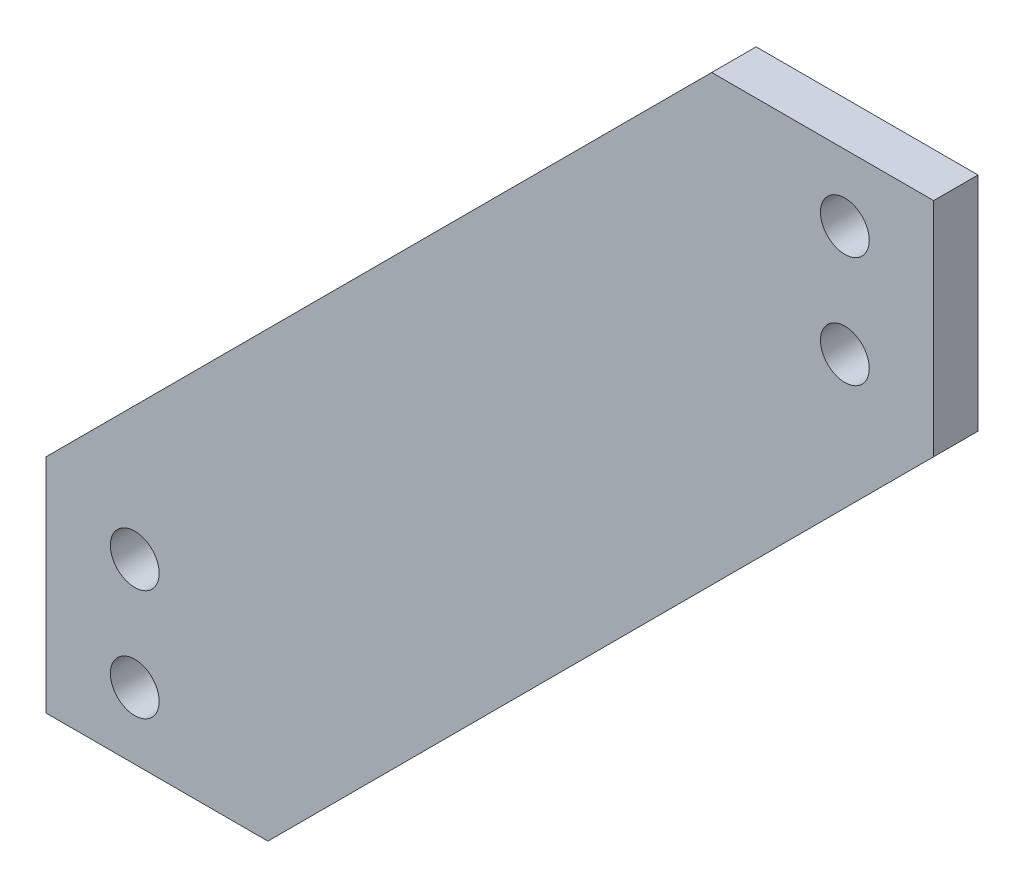
SolidWorks part; units mm, degrees
ref_plane "Front" through (0, 0, 0) normal (0, 0, 1) x (1, 0, 0)
ref_plane "Top" through (0, 0, 0) normal (0, 1, 0) x (1, 0, 0)
ref_plane "Right" through (0, 0, 0) normal (1, 0, 0) x (0, 0, -1)
sketch "Sketch1" plane through (0, 0, 0) normal (0, 0, 1) x (1, 0, 0)
  line L0 (0, 0) -> (20, 0)
  line L1 (20, 0) -> (100, 100)
  line L2 (100, 100) -> (80, 100)
  line L3 (80, 100) -> (0, 0)
  dimension "D1" = 20
  dimension "D2" = 100
  dimension "D3" = 100
extrude "Boss-Extrude1" add sketch "Sketch1" along normal blind 5
sketch "Sketch2" plane through (0, 0, 5) normal (0, 0, 1) x (1, 0, 0)
  line L0 (0, 0) -> (0, 25)
  line L1 (0, 25) -> (75, 100)
  line L2 (75, 100) -> (80, 100)
  line L3 (80, 100) -> (100, 100)
  line L4 (100, 100) -> (100, 75)
  line L5 (100, 75) -> (25, 0)
  line L6 (25, 0) -> (0, 0)
  dimension "D1" = 25
  dimension "D2" = 25
  dimension "D3" = 25
extrude "Boss-Extrude2" add sketch "Sketch2" against normal up to surface (5 mm away) up to face at (50, 50, 0)
hole_wizard "M5 Clearance Hole1" positions "Sketch3" profile "Sketch4" hole size "M5" standard "ISO" end condition through all
sketch "Sketch3" plane through (0, 0, 5) normal (0, 0, 1) x (1, 0, 0)
  line L0 (0, 25) -> (0, 0) construction
  line L1 (0, 0) -> (25, 0) construction
  line L2 (100, 75) -> (100, 100) construction
  line L3 (100, 100) -> (75, 100) construction
  line L4 (10, 20) -> (10, 7.5) construction
  line L6 (90, 92.5) -> (90, 80) construction
  point P0 (10, 20)
  point P2 (90, 80)
  point P14 (10, 7.5)
  point P16 (90, 92.5)
  dimension "D1" = 10
  dimension "D2" = 20
  dimension "D3" = 10
  dimension "D4" = 20
  dimension "D5" = 12.5
  dimension "D6" = 12.5
sketch "Sketch4" plane through (10, 20, 5) normal (1, 0, 0) x (0, -1, 0)
  line L0 (0, 0) -> (0, 5)
  line L1 (0, 5) -> (2.75, 5)
  line L2 (2.75, 5) -> (2.75, 0)
  line L5 (2.75, 0) -> (0, 0)
  line L11 (0, -6.35) -> (0, 107.95) construction
  dimension "Thru Hole Dia." = 5.5
  dimension "Thru Hole Depth" = 5
